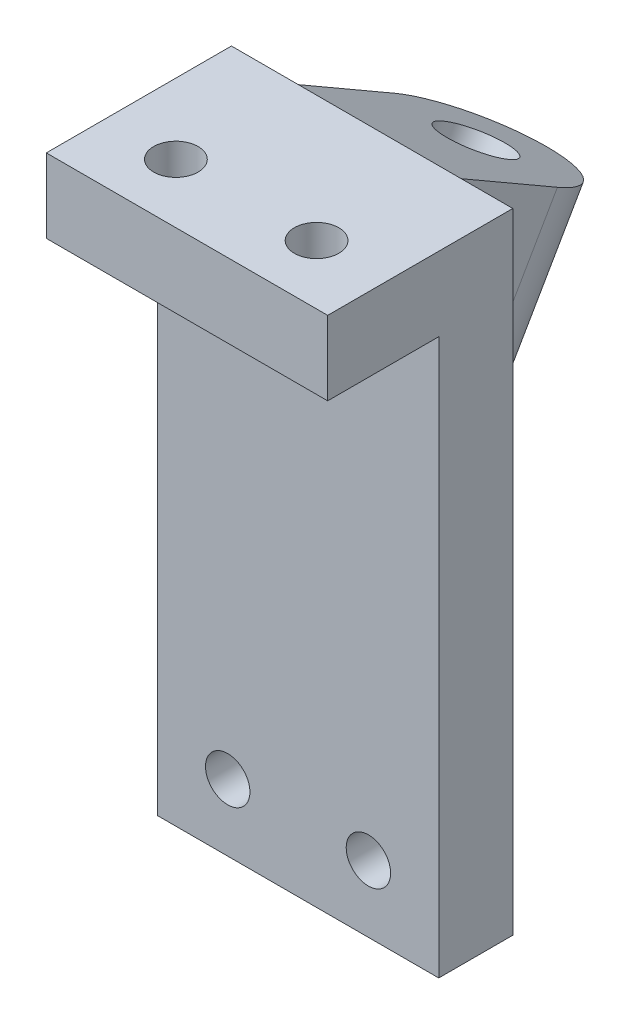
SolidWorks part; units mm, degrees
ref_plane "Front Plane" through (0, 0, 0) normal (0, 0, 1) x (1, 0, 0)
ref_plane "Top Plane" through (0, 0, 0) normal (0, 1, 0) x (1, 0, 0)
ref_plane "Right Plane" through (0, 0, 0) normal (1, 0, 0) x (0, 0, -1)
sketch "Sketch1" plane through (0, 0, 0) normal (0, 1, 0) x (1, 0, 0)
  line L0 (0, -55) -> (0, 55) construction
  line L1 (-38, -25) -> (38, -25)
  line L2 (-38, -25) -> (-38, 25)
  line L3 (-38, 25) -> (38, 25)
  line L4 (38, -25) -> (38, 25)
  line L5 (-38, -25) -> (38, 25) construction
  line L6 (-38, 25) -> (38, -25) construction
  circle A0 centre (-19, -9) radius 6
  circle A1 centre (19, -9) radius 6
  point P0 (0, 0)
  dimension "D3" = 12
  dimension "D1" = 76
  dimension "D2" = 50
  dimension "D4" = 34
  dimension "D5" = 38
extrude "Boss-Extrude1" add sketch "Sketch1" along normal blind 20
sketch "Sketch2" plane through (0, 0, 0) normal (0, -1, 0) x (1, 0, 0)
  line L0 (38, 25) -> (38, -25) construction
  line L1 (-38, -25) -> (38, -25)
  line L2 (-38, -25) -> (-38, -5)
  line L3 (-38, -5) -> (38, -5)
  line L4 (38, -25) -> (38, -5)
  dimension "D1" = 20
extrude "Boss-Extrude2" add sketch "Sketch2" along normal blind 150
sketch "Sketch3" plane through (0, 0, -25) normal (0, 0, -1) x (-1, 0, 0)
  line L0 (38, -150) -> (-38, -150) construction
  line L1 (0, 27.5) -> (0, -27.5) construction
  circle A0 centre (-19, -132) radius 6
  circle A1 centre (19, -132) radius 6
  dimension "D1" = 12
  dimension "D2" = 18
  dimension "D3" = 38
extrude "Cut-Extrude1" cut sketch "Sketch3" against normal blind 150
ref_plane "Plane1" through (0, 0, 0) normal (1, 0, 0) x (0, 0, -1)
sketch "Sketch4" plane through (0, 0, 0) normal (1, 0, 0) x (0, 0, -1)
  line L0 (25, 20) -> (50.9808, 5) construction
  line L1 (25, 20) -> (25, -150) construction
  dimension "D1" = 60
  dimension "D2" = 30
ref_plane "Plane2" through (0, 25.8253, -14.9103) normal (0, -0.866, 0.5) x (1, 0, 0)
sketch "Sketch5" plane through (0, 25.8253, -14.9103) normal (0, -0.866, 0.5) x (1, 0, 0)
  line L0 (38, -11.6506) -> (-38, -11.6506) construction
  line L2 (-19.932, -11.6506) -> (24.068, -11.6506)
  line L3 (-19.932, -11.6506) -> (-19.932, -41.6506)
  line L5 (24.068, -11.6506) -> (24.068, -41.6506)
  arc A0 (-19.932, -41.6506) -> (24.068, -41.6506) centre (2.068, -41.6506) ccw
  circle A1 centre (2.068, -41.6506) radius 9
  dimension "D2" = 44
  dimension "D4" = 18
  dimension "D1" = 30
  dimension "D3" = 30
extrude "Boss-Extrude3" add sketch "Sketch5" along normal up to next
